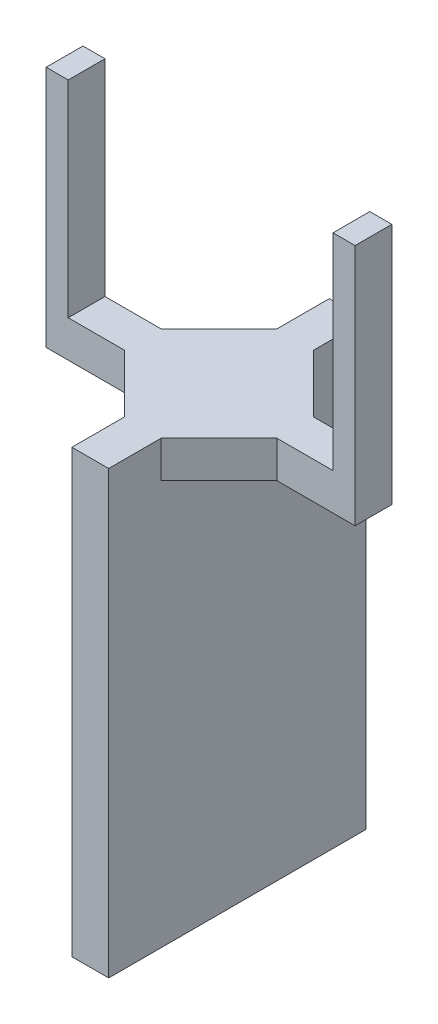
SolidWorks part; units mm, degrees
ref_plane "Front Plane" through (0, 0, 0) normal (0, 0, 1) x (1, 0, 0)
ref_plane "Top Plane" through (0, 0, 0) normal (0, 1, 0) x (1, 0, 0)
ref_plane "Right Plane" through (0, 0, 0) normal (1, 0, 0) x (0, 0, -1)
sketch "Sketch1" plane through (0, 0, 0) normal (0, 0, 1) x (1, 0, 0)
  line L0 (0, -6.998) -> (0, -0.648)
  line L1 (0, -0.648) -> (-22.86, -0.648)
  line L2 (-22.86, -0.648) -> (-22.86, 34.912)
  line L3 (-22.86, 34.912) -> (-26.67, 34.912)
  line L4 (-26.67, 34.912) -> (-26.67, -6.998)
  line L5 (-26.67, -6.998) -> (0, -6.998)
  dimension "D1" = 6.35
  dimension "D2" = 3.81
  dimension "D3" = 35.56
  dimension "D4" = 22.86
extrude "Boss-Extrude1" add sketch "Sketch1" along normal blind 3.175
mirror "Mirror1" about plane through (0, 0, 0) normal (0, 0, 1) of "Boss-Extrude1"
mirror "Mirror2" about plane through (0, 0, 0) normal (1, 0, 0) of "Mirror1", "Boss-Extrude1"
sketch "Sketch2" plane through (0, 0, 0) normal (1, 0, 0) x (0, 0, -1)
  line L0 (3.175, -0.648) -> (-3.175, -0.648) construction
  line L1 (-22.225, -76.848) -> (22.225, -76.848)
  line L2 (-22.225, -76.848) -> (-22.225, -0.648)
  line L3 (-22.225, -0.648) -> (22.225, -0.648)
  line L4 (22.225, -76.848) -> (22.225, -0.648)
  line L5 (-22.225, -76.848) -> (22.225, -0.648) construction
  line L6 (-22.225, -0.648) -> (22.225, -76.848) construction
  point P0 (0, -38.748)
  point P5 (0, -31.1931)
  dimension "D1" = 44.45
  dimension "D2" = 76.2
extrude "Boss-Extrude2" add sketch "Sketch2" along normal blind 3.175
mirror "Mirror3" about plane through (0, 0, 0) normal (1, 0, 0) of "Boss-Extrude2"
chamfer "Chamfer1" distance 10 angle 45 4 edges at (3.175, -3.823, -3.175) (3.175, -3.823, 3.175) (-3.175, -3.823, -3.175) (-3.175, -3.823, 3.175)
